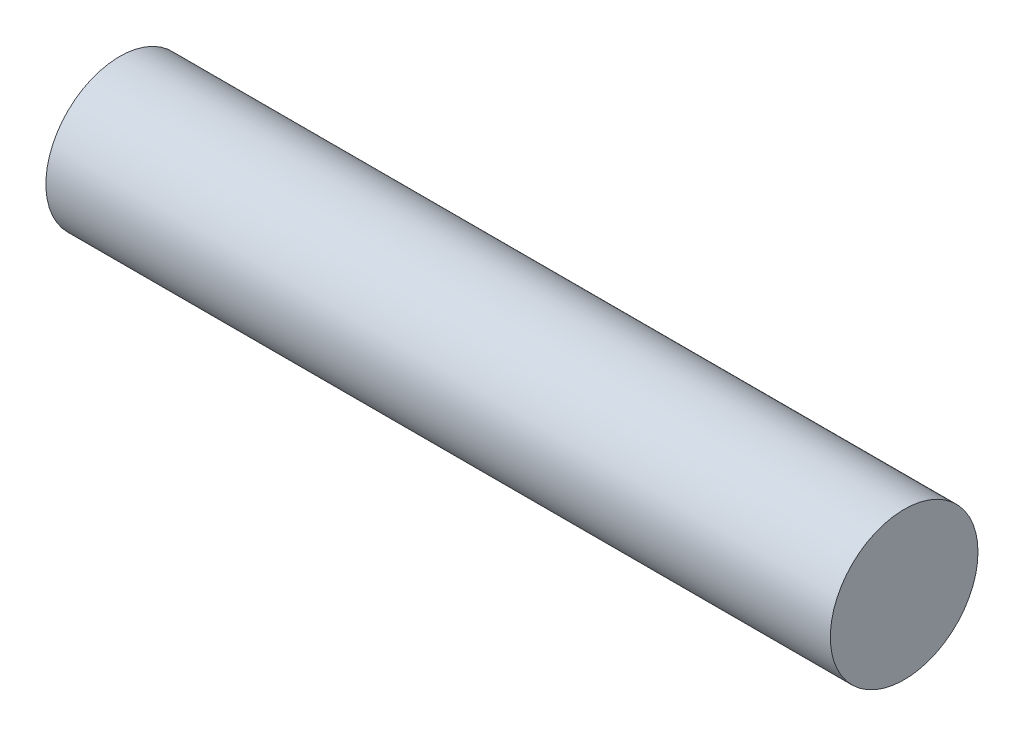
SolidWorks part; units mm, degrees
ref_plane "Front Plane" through (0, 0, 0) normal (0, 0, 1) x (1, 0, 0)
ref_plane "Top Plane" through (0, 0, 0) normal (0, 1, 0) x (1, 0, 0)
ref_plane "Right Plane" through (0, 0, 0) normal (1, 0, 0) x (0, 0, -1)
sketch "Sketch1" plane through (0, 0, 0) normal (1, 0, 0) x (0, 0, -1)
  circle A0 centre (0, 0) radius 80
extrude "FoamBody" add sketch "Sketch1" along normal mid plane 850 separate body
sketch "Sketch2" plane through (0, 0, 0) normal (0, 1, 0) x (1, 0, 0)
  line L1 (-351.5, -30) -> (-186.5, -30)
  line L2 (-351.5, -30) -> (-351.5, 30)
  line L3 (-351.5, 30) -> (-186.5, 30)
  line L4 (-186.5, -30) -> (-186.5, 30)
extrude "battery bay" cut sketch "Sketch2" against normal blind 60 from offset 10
sketch "Sketch3" plane through (0, 0, 0) normal (0, 1, 0) x (1, 0, 0)
  line L1 (-300, -40) -> (-150, -40)
  line L2 (-300, -40) -> (-300, 40)
  line L3 (-300, 40) -> (-150, 40)
  line L4 (-150, -40) -> (-150, 40)
extrude "Foam" cut sketch "Sketch3" along normal blind 35 from offset 10
sketch "Sketch4" plane through (0, 0, 0) normal (0, 1, 0) x (1, 0, 0)
  line L1 (-346.5, -24) -> (-191.5, -24)
  line L2 (-346.5, -24) -> (-346.5, 24)
  line L3 (-346.5, 24) -> (-191.5, 24)
  line L4 (-191.5, -24) -> (-191.5, 24)
extrude "Battery" add sketch "Sketch4" along normal blind 3 and the other way blind 47 separate body
sketch "Sketch5" plane through (0, 0, 0) normal (0, 1, 0) x (1, 0, 0)
  line L1 (-251, -16) -> (-199, -16)
  line L2 (-251, -16) -> (-251, 16)
  line L3 (-251, 16) -> (-199, 16)
  line L4 (-199, -16) -> (-199, 16)
extrude "FC" add sketch "Sketch5" along normal blind 17 from offset 13 separate body
